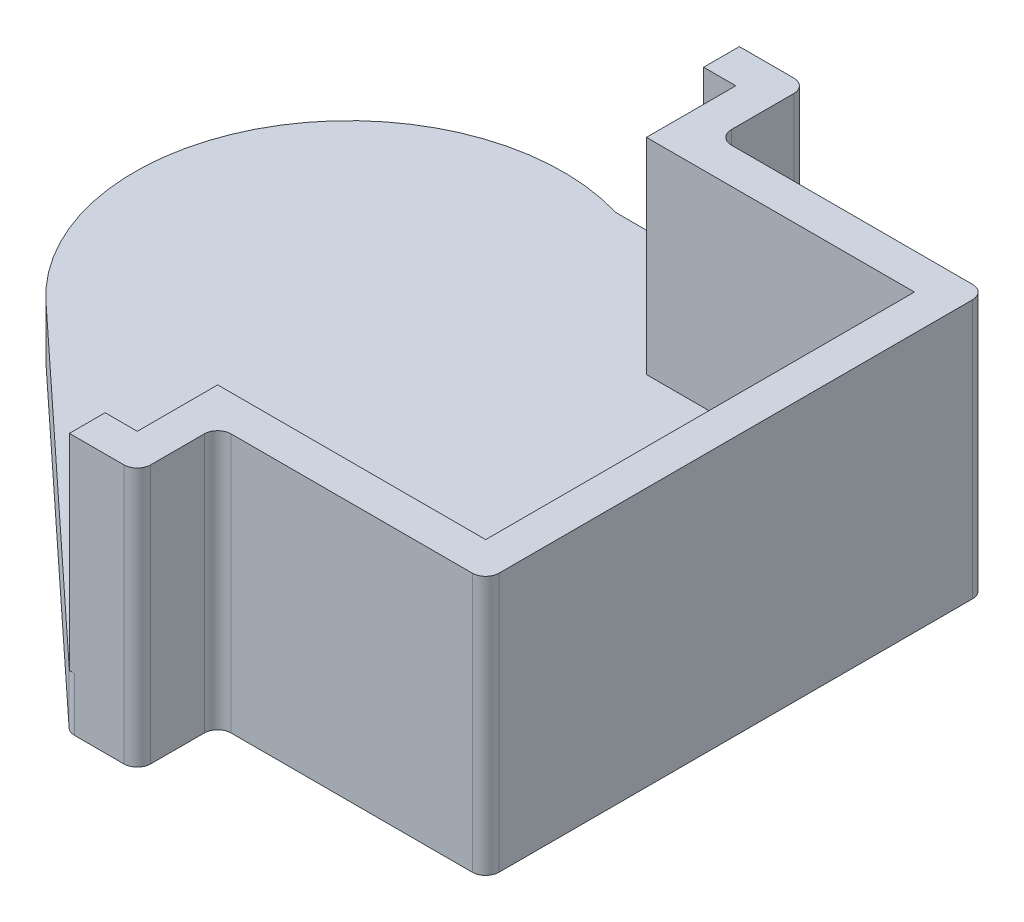
SolidWorks part; units mm, degrees
ref_plane "Front Plane" through (0, 0, 0) normal (0, 0, 1) x (1, 0, 0)
ref_plane "Top Plane" through (0, 0, 0) normal (0, 1, 0) x (1, 0, 0)
ref_plane "Right Plane" through (0, 0, 0) normal (1, 0, 0) x (0, 0, -1)
sketch "Sketch1" plane through (0, 0, 0) normal (0, 1, 0) x (1, 0, 0)
  line L0 (3.35, 28) -> (3.35, 23)
  line L9 (0, 0) -> (3.35, 0)
  line L10 (0, 0) -> (0, 23)
  line L11 (0, 23) -> (3.35, 23)
  line L12 (19.65, 0) -> (19.65, 23)
  line L14 (4.65, 0) -> (4.65, -5)
  line L15 (4.65, -5) -> (3.35, -5)
  line L16 (3.35, 0) -> (3.35, -5)
  line L17 (4.65, -5) -> (3.35, -5)
  line L18 (4.65, -5) -> (4.65, 28) construction
  line L19 (4.65, 28) -> (3.35, 28)
  line L20 (3.35, -5) -> (3.35, 28) construction
  line L21 (4.65, 28) -> (4.65, 23)
  line L22 (4.65, 0) -> (19.65, 0)
  line L23 (4.65, 23) -> (19.65, 23)
  line L24 (2.85, 28) -> (2.85, 23.5)
  line L25 (-0.5, 23.5) -> (2.85, 23.5)
  line L26 (-0.5, -0.5) -> (-0.5, 23.5)
  line L27 (-0.5, -0.5) -> (2.85, -0.5)
  line L28 (2.85, -0.5) -> (2.85, -5)
  line L29 (5.15, -0.5) -> (5.15, -5)
  line L30 (5.15, -0.5) -> (20.15, -0.5)
  line L31 (20.15, -0.5) -> (20.15, 23.5)
  line L32 (5.15, 23.5) -> (20.15, 23.5)
  line L33 (5.15, 28) -> (5.15, 23.5)
  line L34 (4.65, -4.5) -> (3.35, -4.5)
  line L35 (4.65, -4.5) -> (3.35, -4.5)
  line L37 (5.15, -5) -> (5.15, 28)
  line L38 (3.85, -5) -> (3.85, 28)
  line L39 (2.85, -5) -> (3.35, -5)
  line L40 (5.15, -5) -> (4.65, -5)
  line L41 (3.35, 28) -> (5.15, 28)
  line L42 (4.65, 28) -> (3.35, 28)
  line L43 (5.15, 28) -> (5.15, 28.5)
  line L46 (2.85, 28) -> (2.85, 28.5)
  line L47 (2.85, 28.5) -> (5.15, 28.5)
  line L48 (5.15, 28) -> (5.15, 28.5)
  dimension "D1" = 23
  dimension "D2" = 19.65
  dimension "D3" = 15
  dimension "D4" = 1.3
  dimension "D5" = 5
  dimension "D6" = 5
  dimension "D7" = 0.5
sketch "Sketch3" plane through (0, 0, 0) normal (0, 1, 0) x (1, 0, 0)
  line L1 (3.35, -5) -> (7.15, -5)
  line L2 (3.35, -5) -> (3.35, 28)
  line L3 (3.35, 28) -> (7.15, 28)
  line L4 (7.15, -5) -> (7.15, -2.5)
  line L5 (4.65, 28) -> (3.35, 28) construction
  line L6 (7.15, 25.5) -> (7.15, 28)
  line L7 (4.65, -5) -> (3.35, -5) construction
  line L8 (7.15, 25.5) -> (22.15, 25.5)
  line L10 (7.15, -2.5) -> (22.15, -2.5)
  line L11 (22.15, 25.5) -> (22.15, -2.5)
  line L12 (4.65, 23) -> (19.65, 23) construction
  line L13 (19.65, 0) -> (19.65, 23) construction
  line L14 (4.65, 0) -> (19.65, 0) construction
  line L15 (4.65, 0) -> (4.65, -5) construction
  point P20 (7.15, -3.75)
  dimension "D1" = 2.5
  dimension "D2" = 2.5
  dimension "D3" = 2.5
  dimension "D4" = 2.5
sketch "Sketch9" plane through (0, 0, 0) normal (0, 1, 0) x (1, 0, 0)
  line L0 (3.35, 28) -> (3.35, 23)
  line L9 (0, 0) -> (3.35, 0)
  line L10 (0, 0) -> (0, 23)
  line L11 (0, 23) -> (3.35, 23)
  line L12 (19.65, 0) -> (19.65, 23)
  line L14 (4.65, 0) -> (4.65, -4.5)
  line L15 (4.65, -5) -> (3.35, -5)
  line L16 (3.35, 0) -> (3.35, -4.5)
  line L17 (4.65, -5) -> (3.35, -5)
  line L18 (4.65, -4.5) -> (4.65, 28) construction
  line L19 (4.65, 28) -> (3.35, 28)
  line L20 (3.35, -4.5) -> (3.35, 28) construction
  line L21 (4.65, 28) -> (4.65, 23)
  line L22 (4.65, 0) -> (19.65, 0)
  line L23 (4.65, 23) -> (19.65, 23)
  line L24 (4.65, 28) -> (3.35, 28)
  line L25 (5.15, -5) -> (3.35, -5)
  line L26 (7.15, -5) -> (7.15, -6.25)
  line L27 (6.4, -7) -> (3.35, -7)
  line L28 (3.35, -5) -> (3.35, -7)
  line L29 (5.15, -0.5) -> (5.15, -5)
  line L30 (5.15, -0.5) -> (20.15, -0.5)
  line L31 (20.15, -0.5) -> (20.15, 23.5)
  line L32 (5.15, 23.5) -> (20.15, 23.5)
  line L33 (5.15, 28) -> (5.15, 23.5)
  line L34 (4.65, -4.5) -> (3.35, -4.5)
  line L35 (4.65, -4.5) -> (3.35, -4.5)
  line L36 (7.15, 28) -> (7.15, 26.25)
  line L37 (5.15, -5) -> (5.15, -0.5)
  line L38 (3.35, -5) -> (3.35, -7)
  line L40 (5.15, -5) -> (4.65, -5)
  line L41 (3.35, 28) -> (4.65, 28)
  line L42 (4.65, 28) -> (3.35, 28)
  line L43 (5.15, 28) -> (5.15, 28.5)
  line L47 (3.35, 30.5) -> (5.15, 30.5)
  line L48 (5.15, 28) -> (5.15, 28.5)
  line L49 (7.9, 25.5) -> (21.4, 25.5)
  line L50 (22.15, -1.75) -> (22.15, 24.75)
  line L51 (7.9, -2.5) -> (21.4, -2.5)
  line L52 (7.15, -3.25) -> (7.15, -5)
  line L53 (5.15, 23.5) -> (5.15, 28)
  line L54 (7.15, 28) -> (7.15, 29.75)
  line L55 (6.4, 30.5) -> (3.35, 30.5)
  line L57 (5.15, -5) -> (5.15, 28) construction
  line L58 (7.15, -2.5) -> (22.15, -2.5) construction
  line L60 (3.35, 30.5) -> (5.15, 30.5)
  line L61 (3.35, 30.5) -> (3.35, 28.5)
  line L62 (3.35, 28.5) -> (5.15, 28.5)
  line L64 (4.65, 0) -> (4.65, -5) construction
  line L65 (4.65, -5) -> (4.65, 28) construction
  line L66 (7.15, -2.5) -> (7.15, -5) construction
  line L67 (7.15, 28) -> (7.15, 25.5) construction
  line L68 (7.15, 25.5) -> (22.15, 25.5) construction
  line L69 (22.15, -2.5) -> (22.15, 25.5) construction
  arc A0 (7.9, -2.5) -> (7.15, -3.25) centre (7.9, -3.25) ccw
  arc A1 (7.15, 26.25) -> (7.9, 25.5) centre (7.9, 26.25) ccw
  arc A2 (7.15, 29.75) -> (6.4, 30.5) centre (6.4, 29.75) ccw
  arc A3 (21.4, 25.5) -> (22.15, 24.75) centre (21.4, 24.75) cw
  arc A4 (22.15, -1.75) -> (21.4, -2.5) centre (21.4, -1.75) cw
  arc A5 (7.15, -6.25) -> (6.4, -7) centre (6.4, -6.25) cw
  dimension "D10" = 0.75
  dimension "D1" = 23
  dimension "D2" = 19.65
  dimension "D3" = 15
  dimension "D4" = 1.3
  dimension "D5" = 5
  dimension "D6" = 5
  dimension "D7" = 0.5
  dimension "D8" = 2.5
  dimension "D9" = 2
  dimension "D11" = 0.5
extrude "Bracket" add sketch "Sketch9" along normal blind 11.5 contours L61 L62 L43 L33 L32 L31 L30 L29 L25 L15 L28 L27 L26 L52 L51 L50 L49 L36 L54 L55 L47
sketch "Sketch12" plane through (0, 0, 0) normal (0, 1, 0) x (1, 0, 0)
  line L0 (3.1341, -6.7994) -> (-15.1691, 10.209)
  line L2 (-3.4667, 30.5) -> (6.4, 30.5)
  line L3 (7.15, 29.75) -> (7.15, 26.25)
  line L4 (7.9, 25.5) -> (21.4, 25.5)
  line L5 (22.15, 24.75) -> (22.15, -1.75)
  line L6 (21.4, -2.5) -> (7.9, -2.5)
  line L7 (7.15, -3.25) -> (7.15, -6.25)
  line L8 (6.4, -7) -> (3.6447, -7)
  arc A0 (-3.6746, 30.5294) -> (-15.1691, 10.209) centre (-7.0005, 18.9995) ccw
  arc A1 (3.1341, -6.7994) -> (3.6447, -7) centre (3.6447, -6.25) ccw
  arc A2 (7.15, -6.25) -> (6.4, -7) centre (6.4, -6.25) cw
  arc A3 (7.9, -2.5) -> (7.15, -3.25) centre (7.9, -3.25) ccw
  arc A4 (22.15, -1.75) -> (21.4, -2.5) centre (21.4, -1.75) cw
  arc A5 (21.4, 25.5) -> (22.15, 24.75) centre (21.4, 24.75) cw
  arc A6 (7.15, 26.25) -> (7.9, 25.5) centre (7.9, 26.25) ccw
  arc A7 (6.4, 30.5) -> (7.15, 29.75) centre (6.4, 29.75) cw
  arc A8 (-3.4667, 30.5) -> (-3.6746, 30.5294) centre (-3.4667, 31.25) cw
  point P17 (3.35, -7)
  point P22 (7.15, -2.5)
  point P25 (22.15, -2.5)
  point P28 (22.15, 25.5)
  point P31 (7.15, 25.5)
  dimension "D1" = 0.75
extrude "Boss-Extrude1" add sketch "Sketch12" against normal blind 3
sketch "Sketch15" plane through (0, 0, 0) normal (0, 1, 0) x (1, 0, 0)
  circle A1 centre (-7, 19) radius 7.0711
  circle A2 centre (-7, 26.0711) radius 2
  circle A3 centre (0.0711, 19) radius 2
  circle A4 centre (-7, 11.9289) radius 2
  circle A5 centre (-14.0711, 19) radius 2
  point P0 (-7, 19)
  point P9 (-7, 19)
  point P12 (-7, 19)
  point P15 (-7, 19)
  point P18 (-7, 19)
  dimension "D1" = 4
extrude "Boss-Extrude2" add sketch "Sketch15" against normal blind 3.5 from surface at -3 contours A5 | A2 | A4 | A3 starting at face at (7.1197, -3, -11.8189)
